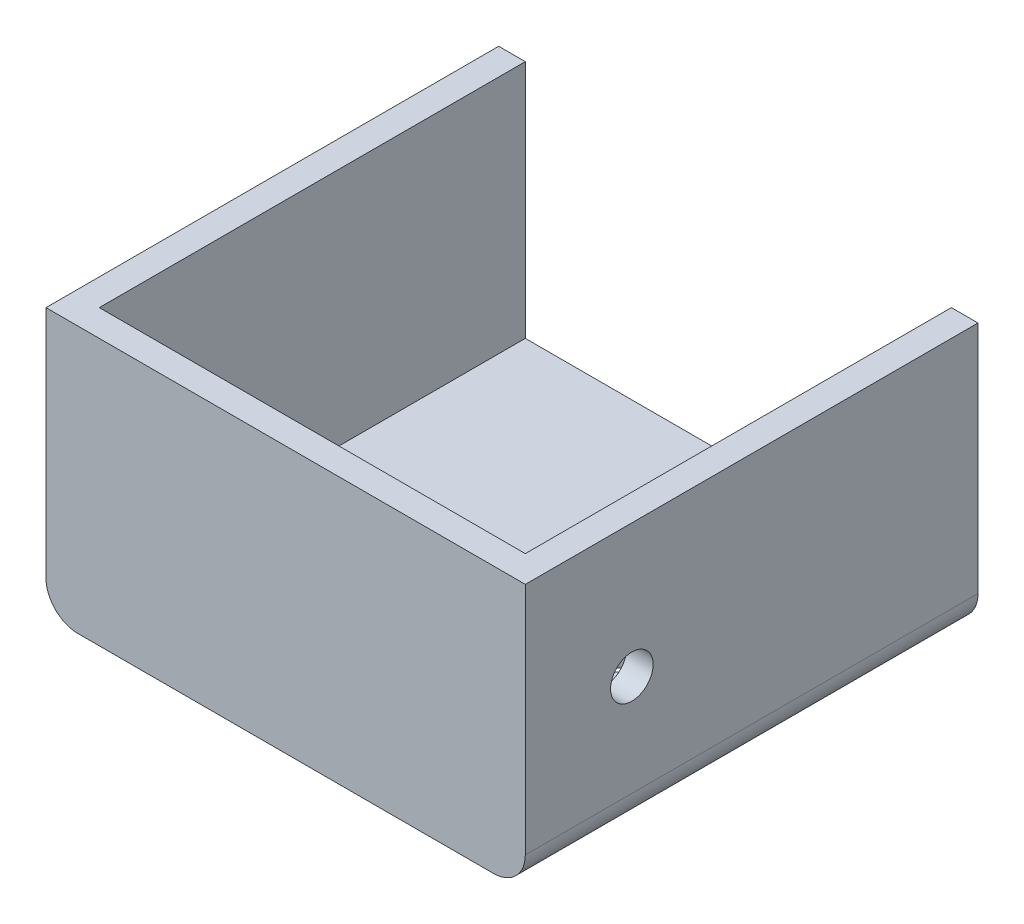
SolidWorks part; units mm, degrees
ref_plane "Alzado" through (0, 0, 0) normal (0, 0, 1) x (1, 0, 0)
ref_plane "Planta" through (0, 0, 0) normal (0, 1, 0) x (1, 0, 0)
ref_plane "Vista lateral" through (0, 0, 0) normal (1, 0, 0) x (0, 0, -1)
sketch "Croquis1" plane through (0, 0, 0) normal (0, 0, 1) x (1, 0, 0)
  line L1 (-22.5, -12.5) -> (22.5, -12.5)
  line L2 (-22.5, -12.5) -> (-22.5, 12.5)
  line L3 (-22.5, 12.5) -> (22.5, 12.5)
  line L4 (22.5, -12.5) -> (22.5, 12.5)
  line L5 (-22.5, -12.5) -> (22.5, 12.5) construction
  line L6 (-22.5, 12.5) -> (22.5, -12.5) construction
  point P0 (0, 0)
  dimension "D1" = 25
  dimension "D2" = 45
extrude "Saliente-Extruir1" add sketch "Croquis1" against normal blind 2.5
sketch "Croquis2" plane through (0, 0, -2.5) normal (0, 0, -1) x (-1, 0, 0)
  line L0 (-22.5, 12.5) -> (-20, 12.5)
  line L1 (-22.5, 12.5) -> (22.5, 12.5) construction
  line L2 (-20, 12.5) -> (-20, -10)
  line L3 (22.5, -12.5) -> (-22.5, -12.5) construction
  line L4 (-20, -12.5) -> (-22.5, -12.5)
  line L5 (-22.5, -12.5) -> (-22.5, 12.5)
  line L6 (22.5, 12.5) -> (20, 12.5)
  line L7 (20, 12.5) -> (20, -10)
  line L8 (20, -12.5) -> (22.5, -12.5)
  line L9 (22.5, -12.5) -> (22.5, 12.5)
  line L10 (-20, -10) -> (20, -10)
  line L11 (-20, -12.5) -> (20, -12.5)
  dimension "D1" = 2.5
  dimension "D2" = 2.5
  dimension "D3" = 2.5
extrude "Saliente-Extruir2" add sketch "Croquis2" along normal blind 40
fillet "Redondeo2" radius 3 1 edges at (22.5, -12.5, -21.25)
fillet "Redondeo3" radius 3 1 edges at (-22.5, -12.5, -21.25)
sketch "Croquis3" plane through (22.5, 0, 0) normal (1, 0, 0) x (0, 0, -1)
  line L0 (0, 12.5) -> (10, 12.5) construction
  line L1 (42.5, 12.5) -> (0, 12.5) construction
  line L2 (10, 12.5) -> (10, 0) construction
  line L3 (10, 0) -> (0, 0) construction
  circle A0 centre (10, 0) radius 2
  dimension "D2" = 4
  dimension "D1" = 10
extrude "Cortar-Extruir1" cut sketch "Croquis3" against normal blind 100
sketch "Croquis4" plane through (0, -12.5, 0) normal (0, -1, 0) x (1, 0, 0)
  line L0 (-19.5, 0) -> (0, 0) construction
  line L1 (-19.5, 0) -> (19.5, 0) construction
  line L2 (0, 0) -> (0, -21.1) construction
  line L3 (0, -21.1) -> (10, -21.1) construction
  line L4 (0, -21.1) -> (-10, -21.1) construction
  circle A0 centre (-10, -21.1) radius 2
  circle A1 centre (10, -21.1) radius 2
  dimension "D1" = 21.1
  dimension "D2" = 10
  dimension "D3" = 10
extrude "Cortar-Extruir2" cut sketch "Croquis4" against normal blind 40
